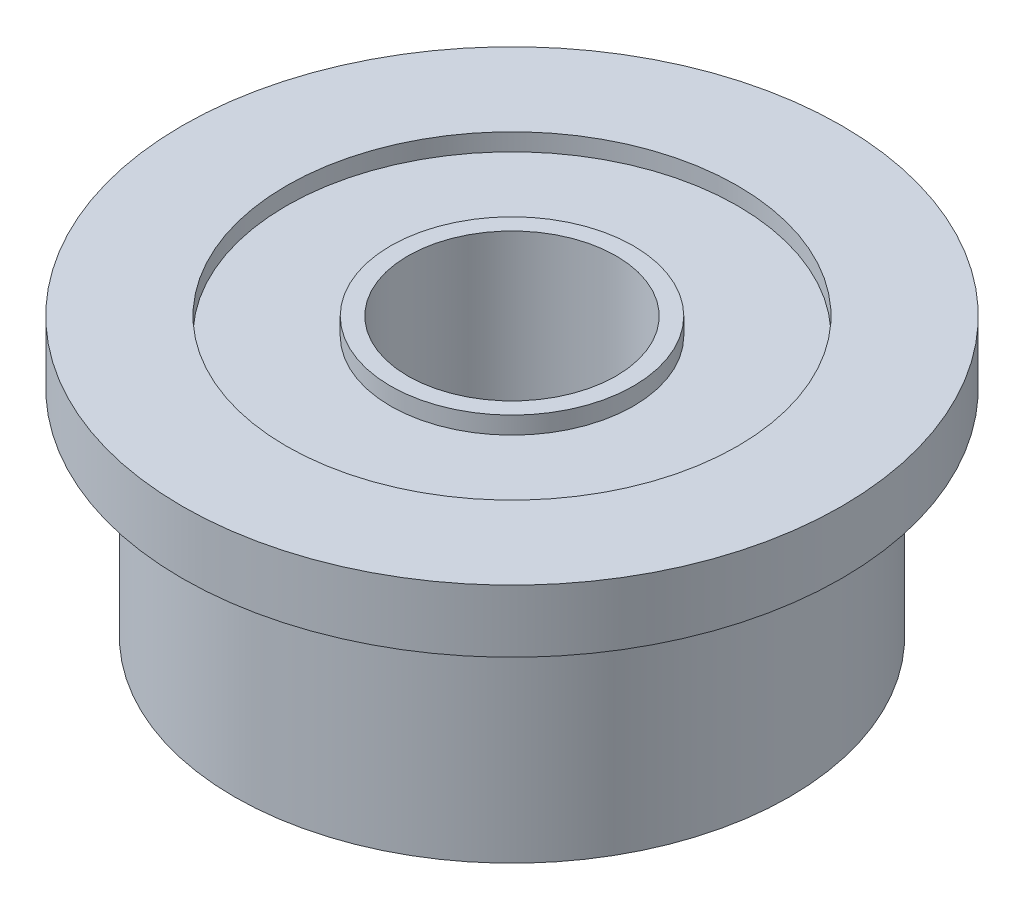
SolidWorks part; units mm, degrees
ref_plane "Front Plane" through (0, 0, 0) normal (0, 0, 1) x (1, 0, 0)
ref_plane "Top Plane" through (0, 0, 0) normal (0, 1, 0) x (1, 0, 0)
ref_plane "Right Plane" through (0, 0, 0) normal (1, 0, 0) x (0, 0, -1)
sketch "Sketch1" plane through (0, 0, 0) normal (0, 1, 0) x (1, 0, 0)
  circle A0 centre (0, 0) radius 1.5
  circle A1 centre (0, 0) radius 4
  dimension "D1" = 8
  dimension "D2" = 3
extrude "Boss-Extrude1" add sketch "Sketch1" along normal blind 4
sketch "Sketch2" plane through (0, 4, 0) normal (0, 1, 0) x (1, 0, 0)
  circle A0 centre (0, 0) radius 1.75
  circle A1 centre (0, 0) radius 3.25
  dimension "D1" = 3.5
  dimension "D2" = 6.5
extrude "Cut-Extrude1" cut sketch "Sketch2" against normal blind 0.25
ref_plane "Plane1" through (0, 2, 0) normal (0, 1, 0) x (1, 0, 0)
mirror "Mirror1" about plane through (0, 2, 0) normal (0, 1, 0) of "Cut-Extrude1"
sketch "Sketch3" plane through (0, 4, 0) normal (0, 1, 0) x (1, 0, 0)
  circle A0 centre (0, 0) radius 4.75
  circle A1 centre (0, 0) radius 4 construction
  circle A2 centre (0, 0) radius 4
  dimension "D1" = 9.5
extrude "Boss-Extrude2" add sketch "Sketch3" against normal blind 0.9
